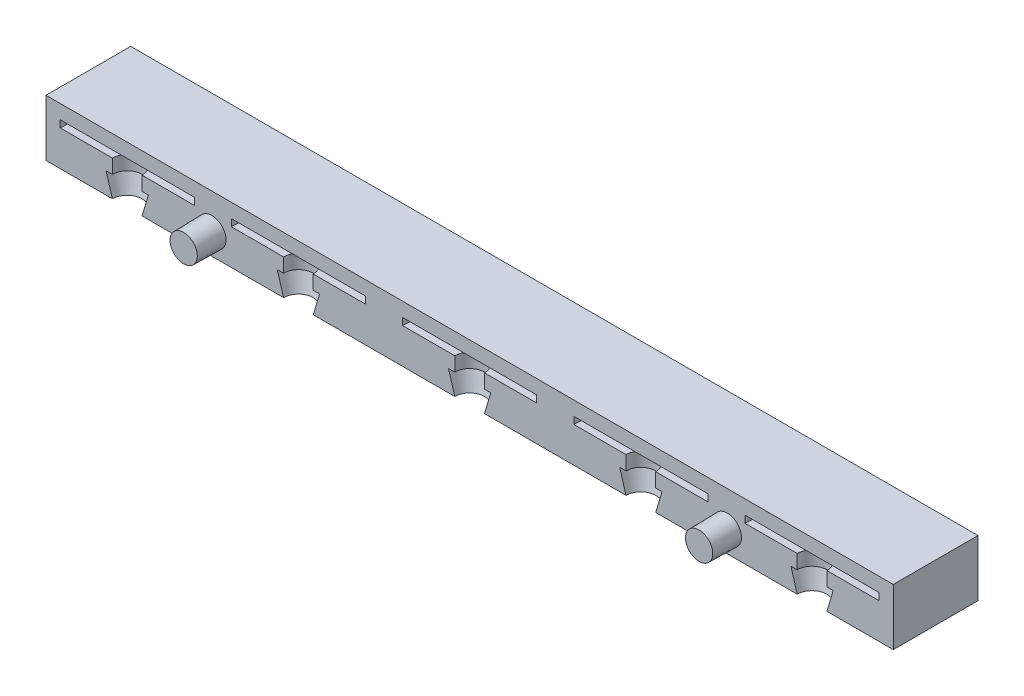
SolidWorks part; units mm, degrees
ref_plane "Front Plane" through (0, 0, 0) normal (0, 0, 1) x (1, 0, 0)
ref_plane "Top Plane" through (0, 0, 0) normal (0, 1, 0) x (1, 0, 0)
ref_plane "Right Plane" through (0, 0, 0) normal (1, 0, 0) x (0, 0, -1)
sketch "Sketch2" plane through (0, 0, 0) normal (0, 0, 1) x (1, 0, 0)
  line L1 (0, 0) -> (120, 0)
  line L2 (0, 0) -> (0, 8)
  line L3 (0, 8) -> (120, 8)
  line L4 (120, 0) -> (120, 8)
  dimension "D1" = 8
  dimension "D2" = 120
extrude "Boss-Extrude1" add sketch "Sketch2" against normal blind 12
sketch "Sketch3" plane through (0, 0, 0) normal (0, 0, 1) x (1, 0, 0)
  line L1 (0, 8) -> (0, 0) construction
  line L2 (8.5, 3) -> (9.4, 3)
  line L3 (9.4, 3) -> (9.4, 5)
  line L4 (9.4, 5) -> (2, 5)
  line L7 (11.5, 6) -> (11.5, 0) construction
  line L8 (8.5, 3) -> (9.4, 0)
  line L9 (9.4, 0) -> (11.5, 0)
  line L10 (0, 0) -> (120, 0) construction
  line L11 (11.5, 0) -> (11.5, 6)
  line L12 (2, 5) -> (2, 6)
  line L13 (2, 6) -> (11.5, 6)
  dimension "D1" = 2
  dimension "D2" = 0
  dimension "D3" = 2.1
  dimension "D4" = 3
  dimension "D5" = 1
  dimension "D6" = 3
  dimension "D7" = 2.1
  dimension "D8" = 0
  dimension "D9" = 9.5
  dimension "D10" = 2
revolve "Cut-Revolve1" cut sketch "Sketch3" angle 360 about L7
pattern_linear "LPattern1" count 5 spacing 24.25 along (1, 0, 0) of "Cut-Revolve1"
sketch "Sketch4" plane through (0, 0, 0) normal (0, 0, 1) x (1, 0, 0)
  line L0 (21, 8) -> (2, 8) construction
  line L1 (11.5, 0) -> (11.5, 8) construction
  line L2 (9.4, 0) -> (13.6, 0) construction
  line L3 (120, 0) -> (120, 8) construction
  line L4 (0, 0) -> (9.4, 0) construction
  line L7 (0, 0) -> (9.4, 0) construction
  circle A0 centre (23.5, 3) radius 2
  circle A2 centre (96.5, 3) radius 2
  dimension "D2" = 4
  dimension "D1" = 23.5
  dimension "D3" = 3
  dimension "D4" = 23.5
  dimension "D5" = 3
extrude "Boss-Extrude2" add sketch "Sketch4" along normal blind 4 draft 1
equation "\"D4@Sketch4\"=\"D1@Sketch4\""
equation "\"D5@Sketch4\"=\"D3@Sketch4\""
